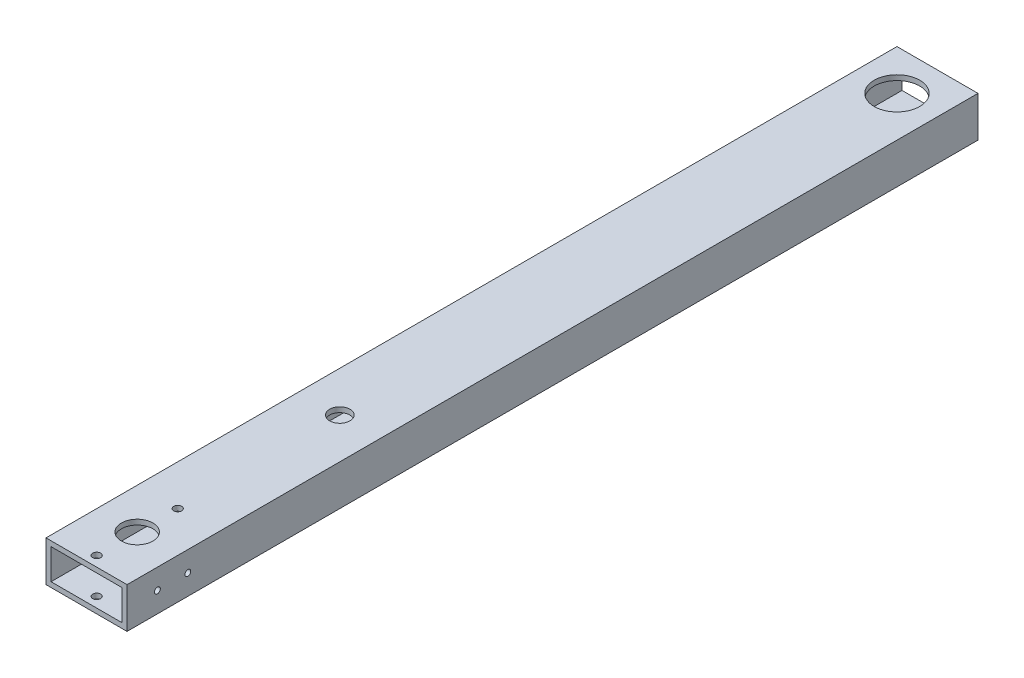
SolidWorks part; units mm, degrees
ref_plane "Front Plane" through (0, 0, 0) normal (0, 0, 1) x (1, 0, 0)
ref_plane "Top Plane" through (0, 0, 0) normal (0, 1, 0) x (1, 0, 0)
ref_plane "Right Plane" through (0, 0, 0) normal (1, 0, 0) x (0, 0, -1)
sketch "Sketch1" plane through (0, 0, 0) normal (0, 0, 1) x (1, 0, 0)
  line L1 (-25.4, -12.7) -> (25.4, -12.7)
  line L2 (-25.4, -12.7) -> (-25.4, 12.7)
  line L3 (-25.4, 12.7) -> (25.4, 12.7)
  line L4 (25.4, -12.7) -> (25.4, 12.7)
  line L5 (-25.4, -12.7) -> (25.4, 12.7) construction
  line L6 (-25.4, 12.7) -> (25.4, -12.7) construction
  point P0 (0, 0)
  dimension "D1" = 50.8
  dimension "D2" = 25.4
extrude "Boss-Extrude1" add sketch "Sketch1" along normal mid plane 533.4
sketch "Sketch2" plane through (0, 0, 266.7) normal (0, 0, 1) x (1, 0, 0)
  line L8 (22.225, -9.525) -> (22.225, 9.525)
  line L9 (22.225, 9.525) -> (-22.225, 9.525)
  line L10 (-22.225, 9.525) -> (-22.225, -9.525)
  line L11 (-22.225, -9.525) -> (22.225, -9.525)
  line L12 (22.225, -9.525) -> (22.225, 9.525)
  line L13 (22.225, 9.525) -> (-22.225, 9.525)
  line L14 (-22.225, 9.525) -> (-22.225, -9.525)
  line L15 (-22.225, -9.525) -> (22.225, -9.525)
  dimension "D1" = 3.175
extrude "Cut-Extrude1" cut sketch "Sketch2" against normal through all
sketch "Sketch5" plane through (0, 12.7, 0) normal (0, 1, 0) x (1, 0, 0)
  line L0 (25.4, -266.7) -> (25.4, 266.7) construction
  line L3 (0, 241.3) -> (0, -234.95) construction
  line L4 (22.225, -266.7) -> (-22.225, -266.7) construction
  circle A0 centre (0, -260.35) radius 2.4892
  circle A1 centre (0, -234.95) radius 9.8488
  circle A2 centre (0, -209.55) radius 2.4892
  circle A3 centre (0, 241.3) radius 14.2875
  point P14 (0, -266.7)
  dimension "D1" = 28.575
  dimension "D2" = 25.4
  dimension "D5" = 4.9784
  dimension "D6" = 19.6977
  dimension "D7" = 4.9784
  dimension "D8" = 25.4
  dimension "D3" = 476.25
  dimension "D9" = 25.4
  dimension "D10" = 6.35
extrude "Cut-Extrude2" cut sketch "Sketch5" against normal blind 508
sketch "Sketch7" plane through (0, 12.7, 0) normal (0, 1, 0) x (1, 0, 0)
  line L0 (-25.4, -266.7) -> (-25.4, 266.7) construction
  circle A0 centre (0, -107.95) radius 6.35
  circle A1 centre (0, -234.95) radius 9.8488 construction
  dimension "D1" = 12.7
  dimension "D2" = 127
  dimension "D3" = 25.4
extrude "Cut-Extrude4" cut sketch "Sketch7" against normal through all
sketch "Sketch8" plane through (25.4, 0, 0) normal (1, 0, 0) x (0, 0, -1)
  line L0 (-266.7, -12.7) -> (-266.7, 12.7) construction
  circle A0 centre (-247.65, 0) radius 1.9812
  circle A1 centre (-228.6, 0) radius 1.9812
  dimension "D1" = 2
  dimension "D2" = 19.05
hole_wizard "#27 (0.144) Diameter Hole1" positions "Sketch10" profile "Sketch9" hole size "#27" standard "ANSI Inch" end condition through all
sketch "Sketch10" plane through (25.4, 0, 0) normal (1, 0, 0) x (0, 0, -1)
  point P0 (-247.65, 0)
  point P3 (-228.6, 0)
sketch "Sketch9" plane through (25.4, 0, 247.65) normal (0, 1, 0) x (0, 0, -1)
  line L0 (0, 0) -> (0, 50.8)
  line L1 (0, 50.8) -> (1.8288, 50.8)
  line L2 (1.8288, 50.8) -> (1.8288, 0)
  line L5 (1.8288, 0) -> (0, 0)
  line L11 (0, -6.35) -> (0, 107.95) construction
  dimension "Thru Hole Dia." = 3.6576
  dimension "Thru Hole Depth" = 50.8
